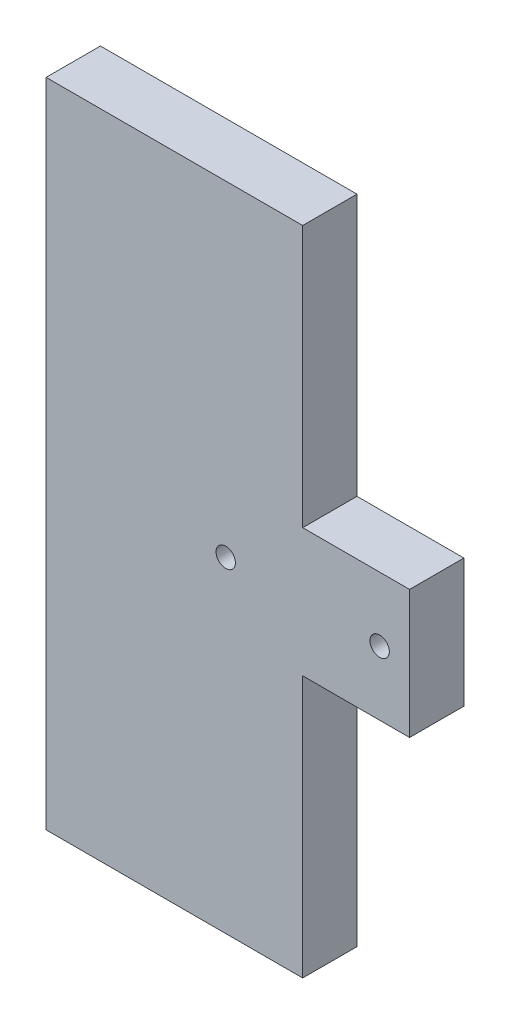
SolidWorks part; units mm, degrees
ref_plane "Front Plane" through (0, 0, 0) normal (0, 0, 1) x (1, 0, 0)
ref_plane "Top Plane" through (0, 0, 0) normal (0, 1, 0) x (1, 0, 0)
ref_plane "Right Plane" through (0, 0, 0) normal (1, 0, 0) x (0, 0, -1)
sketch "Sketch1" plane through (0, 0, 0) normal (0, 0, 1) x (1, 0, 0)
  line L0 (0, -7.5) -> (0, -38.1)
  line L4 (12.5, 7.5) -> (12.5, -7.5)
  line L5 (-30, 38.1) -> (0, 38.1)
  line L6 (-30, 38.1) -> (-30, -38.1)
  line L7 (-30, -38.1) -> (0, -38.1)
  line L8 (0, 38.1) -> (0, 7.5)
  line L9 (0, 7.5) -> (12.5, 7.5)
  line L10 (12.5, -7.5) -> (0, -7.5)
  circle A0 centre (0, 0) radius 4.5 construction
  circle A1 centre (-9, 0) radius 1.1303
  circle A2 centre (9, 0) radius 1.1303
  circle A3 centre (-9, 0) radius 2.3241 construction
  point P0 (0, 0)
  point P9 (12.5, 0)
  dimension "D1" = 9
  dimension "D3" = 2.2606
  dimension "D7" = 4.6482
  dimension "D2" = 12.5
  dimension "D4" = 18
  dimension "D5" = 3.5
  dimension "D6" = 15
  dimension "D8" = 30
  dimension "D9" = 76.2
extrude "Boss-Extrude1" add sketch "Sketch1" along normal blind 6.35
